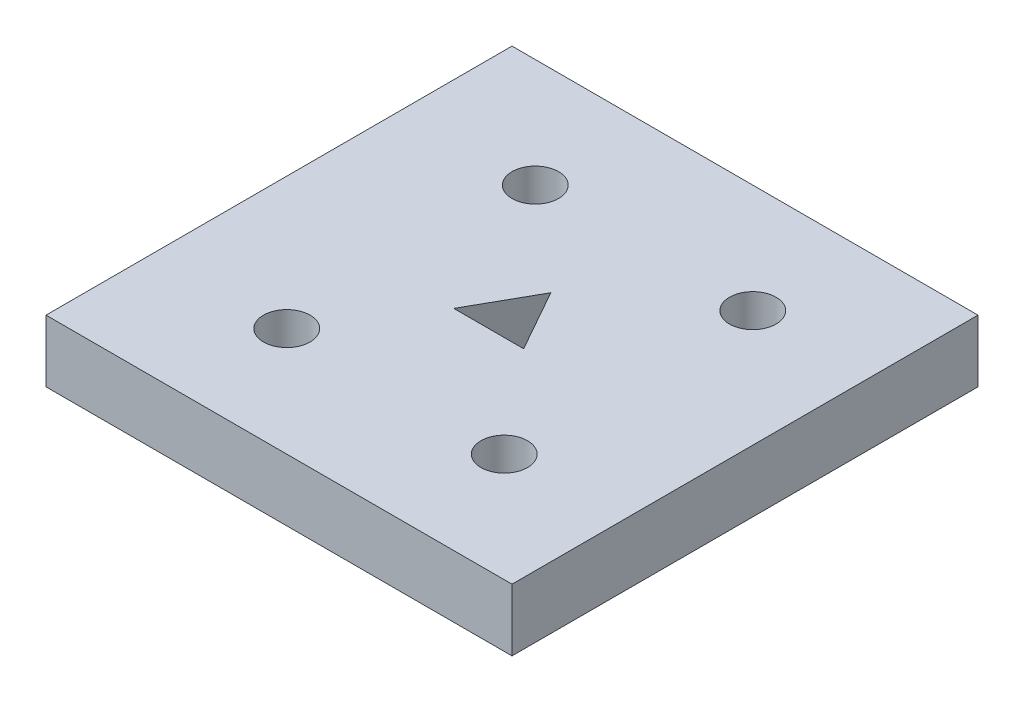
SolidWorks part; units mm, degrees
ref_plane "前视基准面" through (0, 0, 0) normal (0, 0, 1) x (1, 0, 0)
ref_plane "上视基准面" through (0, 0, 0) normal (0, 1, 0) x (1, 0, 0)
ref_plane "右视基准面" through (0, 0, 0) normal (1, 0, 0) x (0, 0, -1)
sketch "草图1" plane through (0, 0, 0) normal (0, 1, 0) x (1, 0, 0)
  line L0 (7, -7) -> (7, -10.1827) construction
  line L1 (0, 0) -> (30, 0)
  line L2 (0, 0) -> (0, -30)
  line L3 (0, -30) -> (30, -30)
  line L4 (30, 0) -> (30, -30)
  line L5 (21, -7) -> (21, -10.1827) construction
  line L6 (15, -12.5) -> (12.75, -16.5)
  line L7 (12.75, -16.5) -> (17.25, -16.5)
  line L8 (17.25, -16.5) -> (15, -12.5)
  line L9 (15, -12.5) -> (15, -22.4885) construction
  line L10 (13.875, -15) -> (16.125, -15) construction
  line L11 (8.5, -5.5) -> (-2.6061, -5.5) construction
  line L12 (8.5, -24.5) -> (-1.2761, -24.5) construction
  circle A0 centre (8.5, -7) radius 1.5
  circle A1 centre (22.5, -7) radius 1.5
  circle A2 centre (22.5, -23) radius 1.5
  circle A3 centre (8.5, -23) radius 1.5
  dimension "D4" = 3
  dimension "D6" = 3
  dimension "D10" = 19
  dimension "D1" = 30
  dimension "D2" = 30
  dimension "D3" = 7
  dimension "D5" = 21
  dimension "D7" = 4
  dimension "D8" = 4.5
  dimension "D9" = 13.5
extrude "凸台-拉伸1" add sketch "草图1" along normal blind 4
